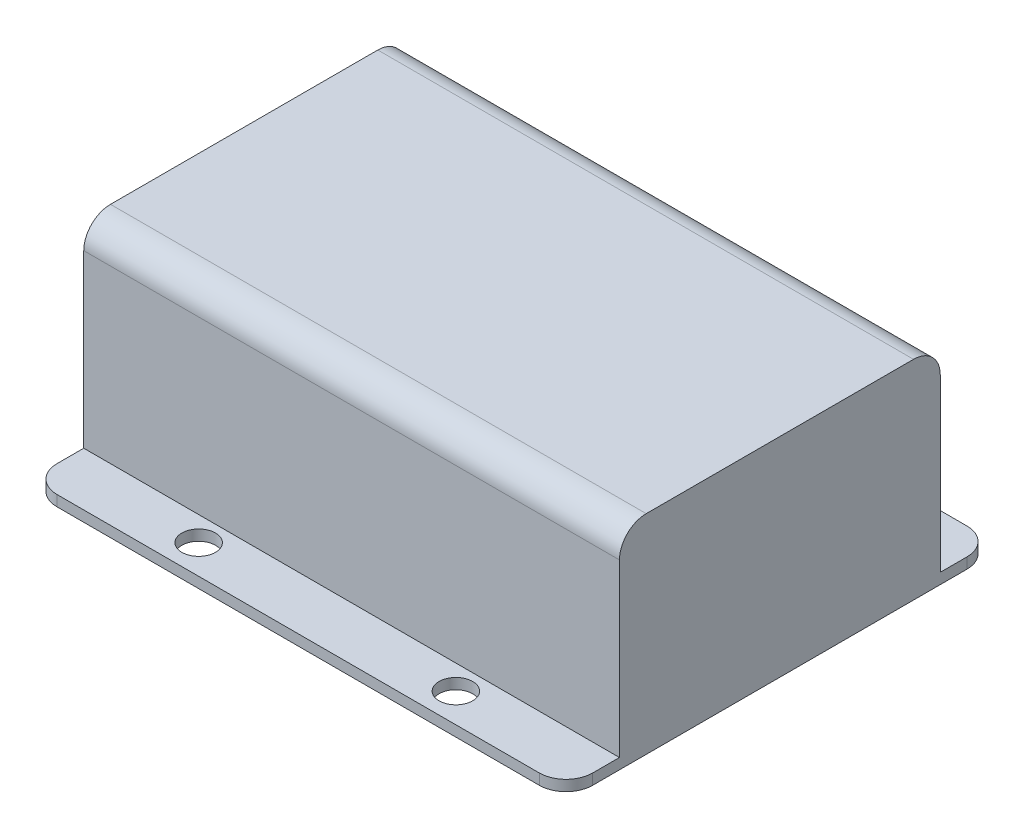
SolidWorks part; units mm, degrees
ref_plane "前视基准面" through (0, 0, 0) normal (0, 0, 1) x (1, 0, 0)
ref_plane "上视基准面" through (0, 0, 0) normal (0, 1, 0) x (1, 0, 0)
ref_plane "右视基准面" through (0, 0, 0) normal (1, 0, 0) x (0, 0, -1)
sketch "草图1" plane through (0, 0, 0) normal (0, 1, 0) x (1, 0, 0)
  line L1 (-50.01, 40) -> (50.19, 40)
  line L2 (-50.01, 40) -> (-50.01, -40)
  line L3 (-50.01, -40) -> (50.19, -40)
  line L4 (50.19, 40) -> (50.19, -40)
  circle A0 centre (-23.96, 34.55) radius 3.14
  circle A1 centre (24.14, 34.55) radius 3.14
  circle A2 centre (24.14, -34.55) radius 3.14
  circle A3 centre (-23.96, -34.55) radius 3.14
  dimension "D5" = 6.28
  dimension "D1" = 100.2
  dimension "D2" = 80
  dimension "D3" = 40
  dimension "D4" = 50.01
  dimension "D6" = 26.05
  dimension "D7" = 5.45
  dimension "D8" = 2
  dimension "D9" = 2
extrude "凸台-拉伸1" add sketch "草图1" along normal blind 2
sketch "草图3" plane through (0, 2, 0) normal (0, 1, 0) x (1, 0, 0)
  line L0 (-50.01, 40) -> (-50.01, -40) construction
  line L1 (-50.01, 30) -> (50.19, 30)
  line L2 (-50.01, 30) -> (-50.01, -30)
  line L3 (-50.01, -30) -> (50.19, -30)
  line L4 (50.19, 30) -> (50.19, -30)
  line L5 (50.19, -40) -> (50.19, 40) construction
  line L6 (50.19, 40) -> (-50.01, 40) construction
  dimension "D1" = 60
  dimension "D2" = 10
extrude "凸台-拉伸2" add sketch "草图3" along normal blind 37
fillet "圆角1" radius 5 4 edges at (-50.01, 1, -40) (50.19, 1, -40) (50.19, 1, 40) (-50.01, 1, 40)
fillet "圆角2" radius 5 2 edges at (0.09, 39, 30) (0.09, 39, -30)
